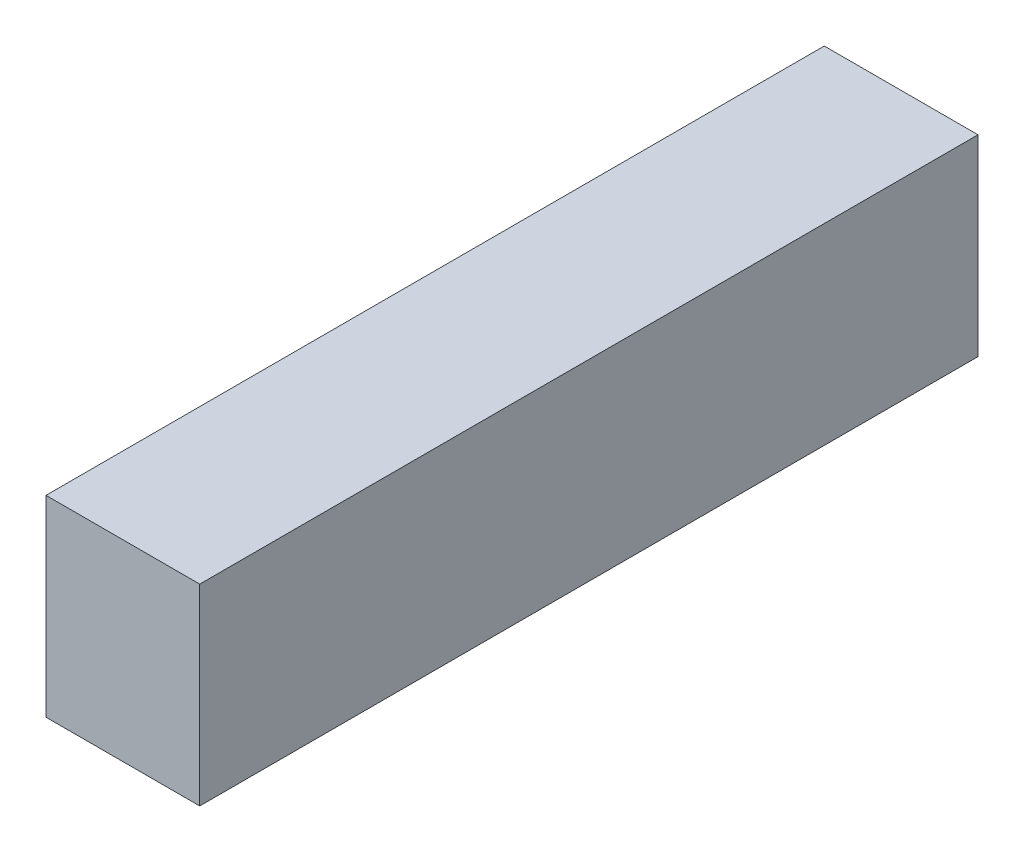
SolidWorks part; units mm, degrees
material "Beech"
ref_plane "Front Plane" through (0, 0, 0) normal (0, 0, 1) x (1, 0, 0)
ref_plane "Top Plane" through (0, 0, 0) normal (0, 1, 0) x (1, 0, 0)
ref_plane "Right Plane" through (0, 0, 0) normal (1, 0, 0) x (0, 0, -1)
sketch "Sketch1" plane through (0, 0, 0) normal (0, 0, 1) x (1, 0, 0)
  line L1 (-191.3402, 195.4639) -> (128.6598, 195.4639)
  line L2 (-191.3402, 195.4639) -> (-191.3402, -204.5361)
  line L3 (-191.3402, -204.5361) -> (128.6598, -204.5361)
  line L4 (128.6598, 195.4639) -> (128.6598, -204.5361)
  dimension "D1" = 320
  dimension "D2" = 400
extrude "Boss-Extrude1" add sketch "Sketch1" along normal blind 1620
